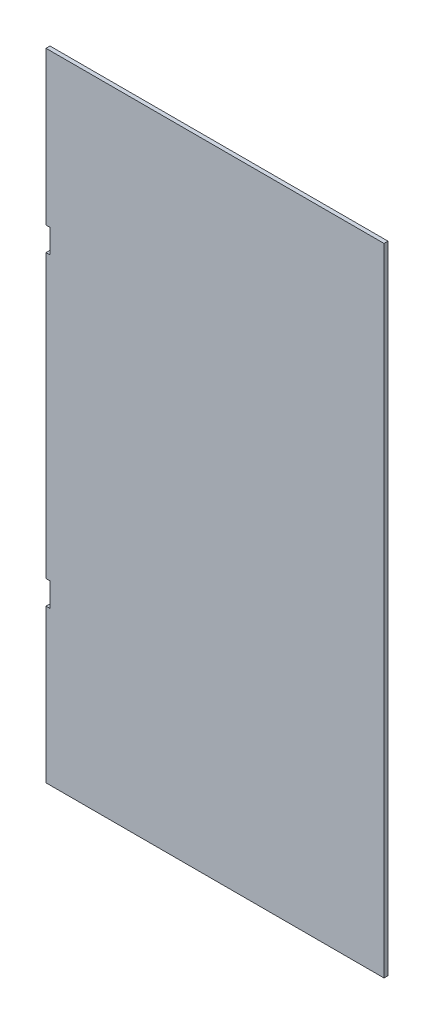
SolidWorks part; units mm, degrees
ref_plane "Plan de face" through (0, 0, 0) normal (0, 0, 1) x (1, 0, 0)
ref_plane "Plan de dessus" through (0, 0, 0) normal (0, 1, 0) x (1, 0, 0)
ref_plane "Plan de droite" through (0, 0, 0) normal (1, 0, 0) x (0, 0, -1)
sketch "Esquisse1" plane through (0, 0, 0) normal (0, 0, 1) x (1, 0, 0)
  line L1 (-200, 400) -> (200, 400)
  line L2 (-200, 400) -> (-200, -400)
  line L3 (-200, -400) -> (200, -400)
  line L4 (200, 400) -> (200, -400)
  line L5 (-200, 400) -> (200, -400) construction
  line L6 (-200, -400) -> (200, 400) construction
  point P0 (0, 0)
  dimension "D1" = 800
  dimension "D2" = 400
extrude "Boss.-Extru.1" add sketch "Esquisse1" along normal blind 5
sketch "Esquisse2" plane through (0, 0, 5) normal (0, 0, 1) x (1, 0, 0)
  line L0 (-200, 0) -> (200, 0) construction
  line L1 (-200, 400) -> (-200, -400) construction
  line L2 (200, -400) -> (200, 400) construction
  line L3 (0, 400) -> (0, -400) construction
  line L4 (200, 400) -> (-200, 400) construction
  line L5 (-200, -400) -> (200, -400) construction
  line L6 (-195, -177.5) -> (-200, -177.5)
  line L7 (-195, 207.5) -> (-200, 207.5)
  line L8 (-195, 207.5) -> (-195, 177.5)
  line L9 (-195, 177.5) -> (-200, 177.5)
  line L10 (-200, 207.5) -> (-200, 177.5)
  line L11 (-195, 207.5) -> (-200, 177.5) construction
  line L12 (-195, 177.5) -> (-200, 207.5) construction
  line L13 (-200, -207.5) -> (-200, -177.5)
  line L14 (-195, -207.5) -> (-200, -207.5)
  line L15 (-195, -207.5) -> (-195, -177.5)
  line L22 (195, 207.5) -> (200, 207.5)
  point P12 (-197.5, 192.5)
  line M13 (-200, 400) -> (-200, -400)
  dimension "D1" = 192.5
  dimension "D2" = 5
  dimension "D3" = 30
extrude "Enlèv. mat.-Extru.1" cut sketch "Esquisse2" against normal blind 5 contours L9 L8 L7 M13 | L14 L15 L6 M13
sketch "Esquisse3" plane through (200, 0, 0) normal (1, 0, 0) x (0, 0, -1)
  line L4 (0, -400) -> (0, 400)
  line L5 (0, 400) -> (-5, 400)
  line L6 (-5, 400) -> (-5, -400)
  line L7 (-5, -400) -> (0, -400)
  line L8 (0, -400) -> (0, 400)
  line L9 (0, 400) -> (-5, 400)
  line L10 (-5, 400) -> (-5, -400)
  line L11 (-5, -400) -> (0, -400)
  dimension "D1" = 0
extrude "Boss.-Extru.2" add sketch "Esquisse3" along normal blind 25
